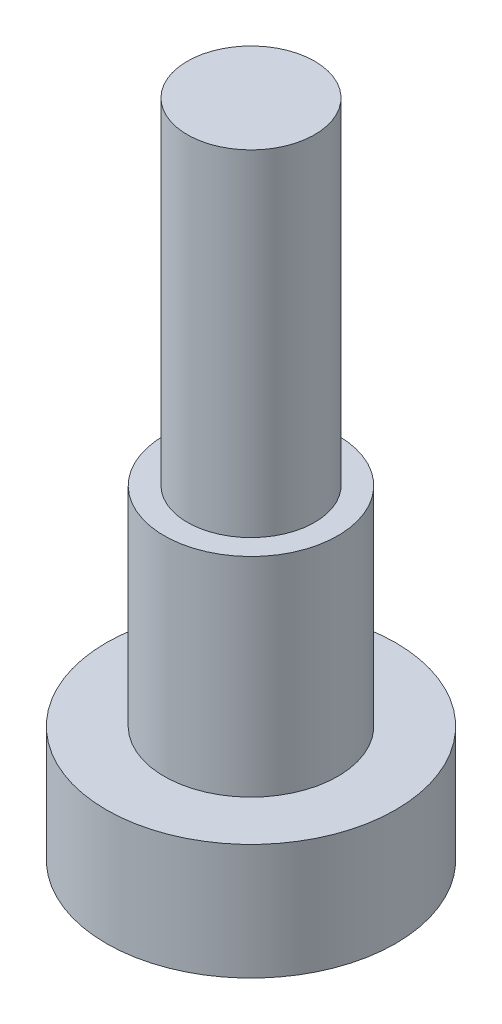
SolidWorks part; units mm, degrees
ref_plane "Plan de face" through (0, 0, 0) normal (0, 0, 1) x (1, 0, 0)
ref_plane "Plan de dessus" through (0, 0, 0) normal (0, 1, 0) x (1, 0, 0)
ref_plane "Plan de droite" through (0, 0, 0) normal (1, 0, 0) x (0, 0, -1)
sketch "Esquisse1" plane through (0, 0, 0) normal (0, 1, 0) x (1, 0, 0)
  circle A0 centre (0, 0) radius 5.5
  dimension "D1" = 11
extrude "Boss.-Extru.1" add sketch "Esquisse1" along normal blind 29
sketch "Esquisse2" plane through (0, 0, 0) normal (0, -1, 0) x (1, 0, 0)
  circle A0 centre (0, 0) radius 7.5
extrude "Boss.-Extru.2" add sketch "Esquisse2" along normal blind 18
sketch "Esquisse3" plane through (0, -18, 0) normal (0, -1, 0) x (1, 0, 0)
  circle A0 centre (0, 0) radius 12.5
  dimension "D1" = 25
extrude "Boss.-Extru.3" add sketch "Esquisse3" along normal blind 10
